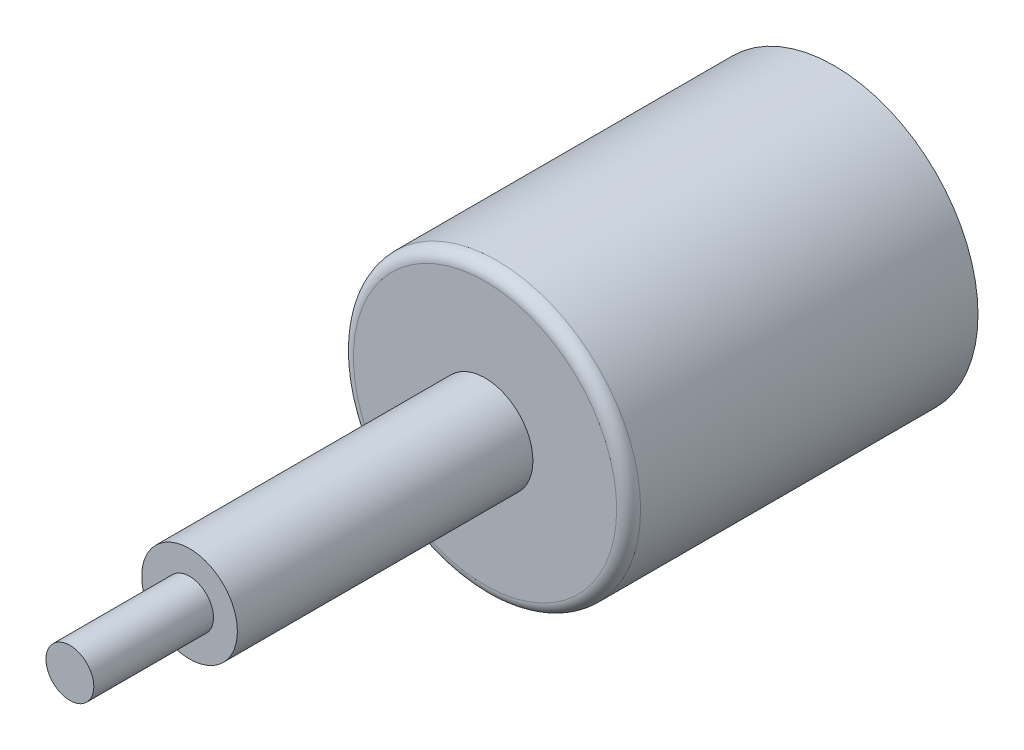
SolidWorks part; units mm, degrees
ref_plane "Plan de face" through (0, 0, 0) normal (0, 0, 1) x (1, 0, 0)
ref_plane "Plan de dessus" through (0, 0, 0) normal (0, 1, 0) x (1, 0, 0)
ref_plane "Plan de droite" through (0, 0, 0) normal (1, 0, 0) x (0, 0, -1)
sketch "Esquisse1" plane through (0, 0, 0) normal (0, 0, 1) x (1, 0, 0)
  circle A0 centre (0, 0) radius 12
extrude "Extrusion1" add sketch "Esquisse1" along normal blind 29.2
fillet "Congé1" radius 1 1 edges at (12, 0, 29.2)
sketch "Esquisse2" plane through (0, 0, 29.2) normal (0, 0, 1) x (1, 0, 0)
  circle A0 centre (0, 0) radius 4
extrude "Extrusion2" add sketch "Esquisse2" along normal blind 24.7
sketch "Esquisse3" plane through (0, 0, 53.9) normal (0, 0, 1) x (1, 0, 0)
  circle A0 centre (0, 0) radius 2
extrude "Extrusion3" add sketch "Esquisse3" along normal blind 10
